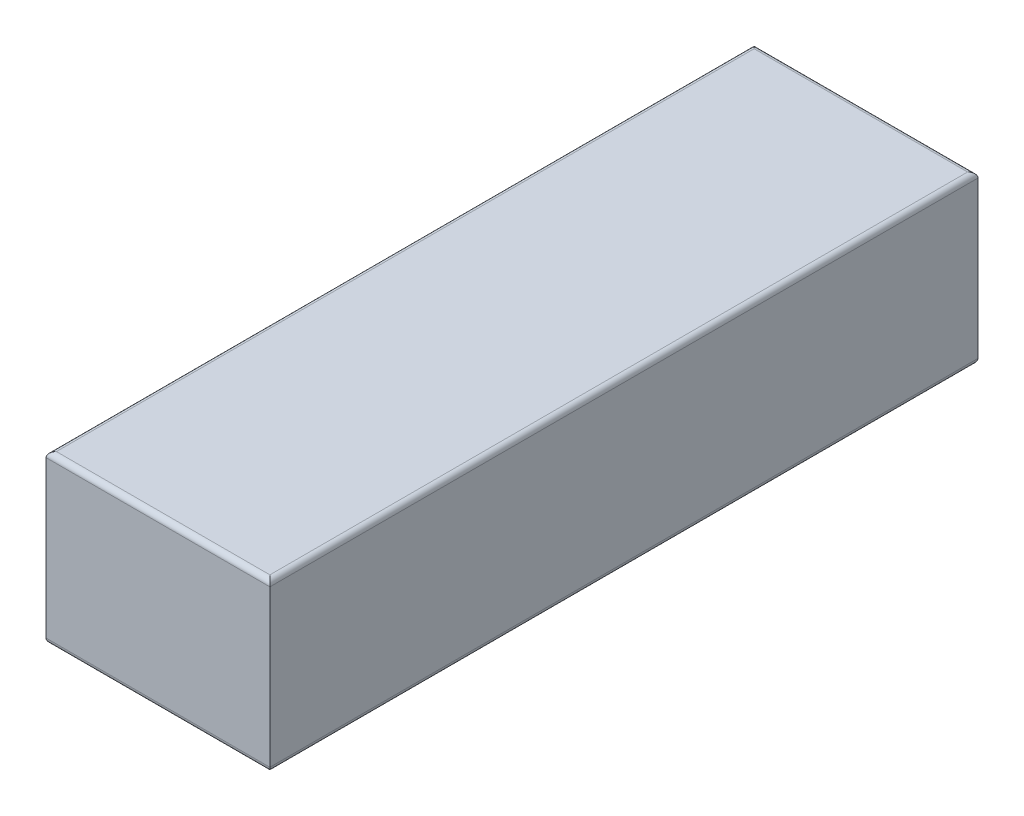
SolidWorks part; units mm, degrees
material "聚脂树脂"
ref_plane "前视基准面" through (0, 0, 0) normal (0, 0, 1) x (1, 0, 0)
ref_plane "上视基准面" through (0, 0, 0) normal (0, 1, 0) x (1, 0, 0)
ref_plane "右视基准面" through (0, 0, 0) normal (1, 0, 0) x (0, 0, -1)
other "Configuration Table"
sketch "草图1" plane through (0, 0, 0) normal (0, 1, 0) x (1, 0, 0)
  line L1 (-21.5, -68) -> (21.5, -68)
  line L2 (-21.5, -68) -> (-21.5, 68)
  line L3 (-21.5, 68) -> (21.5, 68)
  line L4 (21.5, -68) -> (21.5, 68)
  line L5 (-21.5, -68) -> (21.5, 68) construction
  line L6 (-21.5, 68) -> (21.5, -68) construction
  point P0 (0, 0)
  dimension "D1" = 43
  dimension "D2" = 136
extrude "凸台-拉伸1" add sketch "草图1" along normal blind 32
fillet "圆角1" radius 1 8 edges at (0, 0, -68) (-21.5, 0, 0) (0, 0, 68) (21.5, 0, 0) (0, 32, 68) (-21.5, 32, 0) (0, 32, -68) (21.5, 32, 0)
